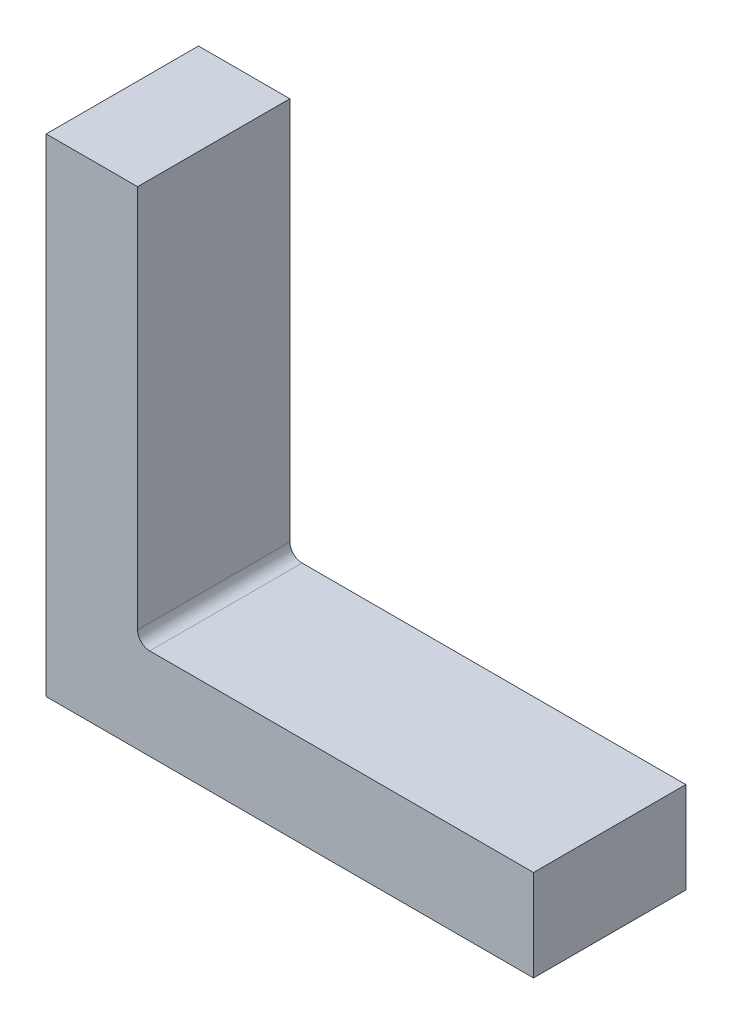
SolidWorks part; units mm, degrees
material "AISI 304"
ref_plane "Front" through (0, 0, 0) normal (0, 0, 1) x (1, 0, 0)
ref_plane "Top" through (0, 0, 0) normal (0, 1, 0) x (1, 0, 0)
ref_plane "Right" through (0, 0, 0) normal (1, 0, 0) x (0, 0, -1)
sketch "Sketch1" plane through (0, 0, 0) normal (0, 0, 1) x (1, 0, 0)
  line L0 (19.05, 101.6) -> (19.05, 19.05)
  line L1 (0, 0) -> (101.6, 0)
  line L2 (0, 0) -> (0, 101.6)
  line L3 (0, 101.6) -> (19.05, 101.6)
  line L4 (101.6, 0) -> (101.6, 19.05)
  line L5 (19.05, 19.05) -> (101.6, 19.05)
  dimension "D1" = 101.6
  dimension "D2" = 101.6
  dimension "D3" = 19.05
  dimension "D4" = 19.05
extrude "Extrude1" add sketch "Sketch1" along normal blind 31.75
fillet "Fillet1" radius 2.54
